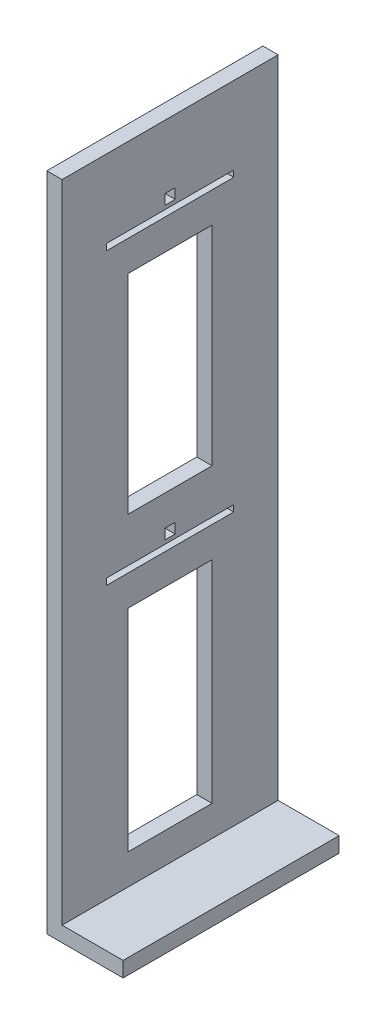
SolidWorks part; units mm, degrees
ref_plane "Front Plane" through (0, 0, 0) normal (0, 0, 1) x (1, 0, 0)
ref_plane "Top Plane" through (0, 0, 0) normal (0, 1, 0) x (1, 0, 0)
ref_plane "Right Plane" through (0, 0, 0) normal (1, 0, 0) x (0, 0, -1)
sketch "Sketch1" plane through (0, 0, 0) normal (0, 1, 0) x (1, 0, 0)
  line L1 (-26, 11.9444) -> (-20, 11.9444)
  line L2 (-26, 11.9444) -> (-26, -5.0556)
  line L3 (-26, -5.0556) -> (-20, -5.0556)
  line L4 (-20, 11.9444) -> (-20, -5.0556)
  dimension "D1" = 6
  dimension "D2" = 17
extrude "Boss-Extrude1" add sketch "Sketch1" along normal blind 1.2
sketch "Sketch2" plane through (0, 1.2, 0) normal (0, 1, 0) x (1, 0, 0)
  line L0 (-26, -5.0556) -> (-20, -5.0556) construction
  line L1 (-26, 11.9444) -> (-24, 11.9444)
  line L2 (-26, 11.9444) -> (-26, -5.0556)
  line L3 (-26, -5.0556) -> (-24, -5.0556)
  line L4 (-24, 11.9444) -> (-24, -5.0556)
  dimension "D1" = 2
extrude "Boss-Extrude2" add sketch "Sketch2" along normal blind 68
sketch "Sketch3" plane through (-24, 0, 0) normal (1, 0, 0) x (0, 0, -1)
  line L0 (-14.365, 23.8) -> (23.9865, 23.8) construction
  line L1 (23.2327, 46.6) -> (-18.6053, 46.6) construction
  line L2 (-5.0556, 1.2) -> (11.9444, 1.2) construction
  line L3 (-5.0556, 69.2) -> (11.9444, 69.2) construction
  line L4 (3.4444, 72.8761) -> (3.4444, -4.8068) construction
  line L6 (3.0444, 23.4) -> (3.8444, 23.4)
  line L7 (3.0444, 23.4) -> (3.0444, 24.2)
  line L8 (3.0444, 24.2) -> (3.8444, 24.2)
  line L9 (3.8444, 23.4) -> (3.8444, 24.2)
  line L10 (3.0444, 23.4) -> (3.8444, 24.2) construction
  line L11 (3.0444, 24.2) -> (3.8444, 23.4) construction
  line L12 (3.0444, 46.2) -> (3.8444, 46.2)
  line L13 (3.0444, 46.2) -> (3.0444, 47)
  line L14 (3.0444, 47) -> (3.8444, 47)
  line L15 (3.8444, 46.2) -> (3.8444, 47)
  line L16 (3.0444, 46.2) -> (3.8444, 47) construction
  line L17 (3.0444, 47) -> (3.8444, 46.2) construction
  line L18 (-1.5556, 23.1) -> (8.4444, 23.1)
  line L19 (-1.5556, 23.1) -> (-1.5556, 22.6)
  line L20 (-1.5556, 22.6) -> (8.4444, 22.6)
  line L21 (8.4444, 23.1) -> (8.4444, 22.6)
  line L22 (-1.5556, 45.9) -> (8.4444, 45.9)
  line L23 (-1.5556, 45.9) -> (-1.5556, 45.4)
  line L24 (-1.5556, 45.4) -> (8.4444, 45.4)
  line L25 (8.4444, 45.9) -> (8.4444, 45.4)
  point P10 (3.4444, 23.8)
  point P15 (3.4444, 46.6)
  dimension "D1" = 22.6
  dimension "D2" = 22.6
  dimension "D3" = 0.8
  dimension "D4" = 0.8
  dimension "D5" = 0.8
  dimension "D6" = 0.8
  dimension "D7" = 0.3
  dimension "D8" = 10
  dimension "D9" = 5
  dimension "D10" = 0.5
  dimension "D11" = 0.5
  dimension "D12" = 0.3
  dimension "D13" = 5
  dimension "D14" = 10
extrude "Cut-Extrude1" cut sketch "Sketch3" against normal up to next
sketch "Sketch4" plane through (-24, 0, 0) normal (1, 0, 0) x (0, 0, -1)
  line L0 (-5.0556, 69.2) -> (-5.0556, 1.2) construction
  line L1 (-5.0556, 52) -> (11.9444, 52)
  line L2 (-5.0556, 52) -> (-5.0556, 69.2)
  line L3 (-5.0556, 69.2) -> (11.9444, 69.2)
  line L4 (11.9444, 52) -> (11.9444, 69.2)
  line L5 (3.8444, 47) -> (3.0444, 47) construction
  line L6 (-5.0556, 1.2) -> (11.9444, 1.2) construction
  line L17 (0.1444, 43) -> (6.7444, 43)
  line L18 (0.1444, 43) -> (0.1444, 26.6)
  line L19 (0.1444, 26.6) -> (6.7444, 26.6)
  line L20 (6.7444, 43) -> (6.7444, 26.6)
  line L21 (0.1444, 20.2) -> (6.7444, 20.2)
  line L22 (0.1444, 20.2) -> (0.1444, 3.6)
  line L23 (0.1444, 3.6) -> (6.7444, 3.6)
  line L24 (6.7444, 20.2) -> (6.7444, 3.6)
  line L25 (-1.5556, 22.6) -> (8.4444, 22.6) construction
  line L26 (-1.5556, 45.4) -> (8.4444, 45.4) construction
  line L27 (3.8444, 24.2) -> (3.0444, 24.2) construction
  point P37 (3.4444, 24.2)
  dimension "D1" = 5
  dimension "D8" = 0
  dimension "D9" = 0
  dimension "D10" = 2.4
  dimension "D11" = 2.4
  dimension "D12" = 2.4
  dimension "D13" = 2.4
extrude "Cut-Extrude3" cut sketch "Sketch4" against normal up to next
sketch "Sketch5" plane through (0, 52, 0) normal (0, 1, 0) x (1, 0, 0)
  line L0 (-24, -5.0556) -> (-24.8, -5.0556)
  line L1 (-24, -5.0556) -> (-24, 11.9444)
  line L2 (-24.8, -5.0556) -> (-24.8, 11.9444)
  line L3 (-24, 11.9444) -> (-24.8, 11.9444)
  line L4 (-26, -5.0556) -> (-24, -5.0556) construction
  dimension "D1" = 17
  dimension "D2" = 0.8
extrude "Cut-Extrude4" cut sketch "Sketch5" against normal up to surface (50.8 mm away) up to face at (-22, 1.2, -3.4444)
